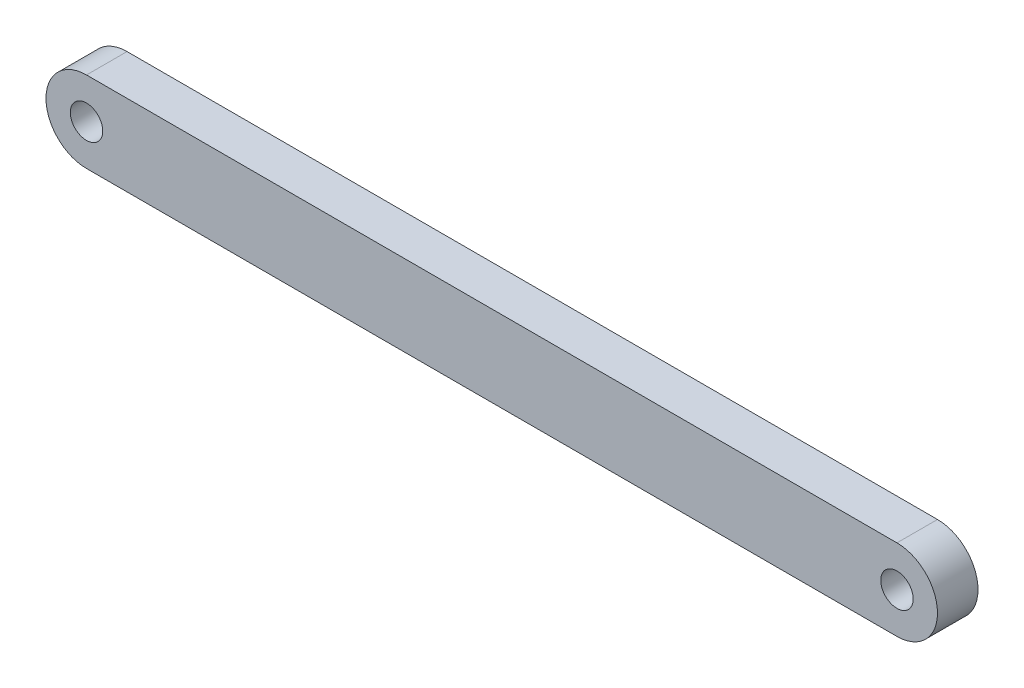
SolidWorks part; units mm, degrees
ref_plane "Alzado" through (0, 0, 0) normal (0, 0, 1) x (1, 0, 0)
ref_plane "Planta" through (0, 0, 0) normal (0, 1, 0) x (1, 0, 0)
ref_plane "Vista lateral" through (0, 0, 0) normal (1, 0, 0) x (0, 0, -1)
sketch "Croquis1" plane through (0, 0, 0) normal (0, 0, 1) x (1, 0, 0)
  line L0 (0, 0) -> (100, 0) construction
  line L2 (0, 5) -> (100, 5)
  line L3 (0, -5) -> (100, -5)
  arc A0 (0, 5) -> (0, -5) centre (0, 0) ccw
  arc A1 (100, -5) -> (100, 5) centre (100, 0) ccw
  circle A2 centre (0, 0) radius 2
  circle A3 centre (100, 0) radius 2
  point P5 (50, 0)
extrude "Saliente-Extruir1" add sketch "Croquis1" along normal blind 5
